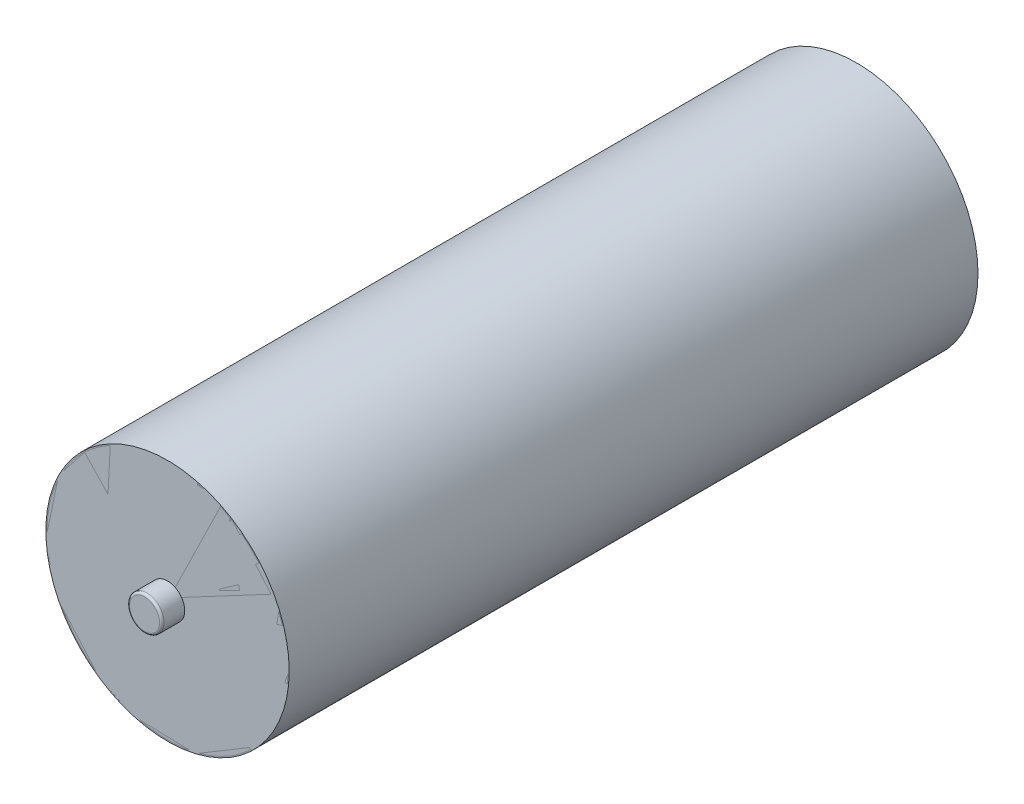
SolidWorks part; units mm, degrees
other "COLL.CYLINDER-Estrusione-Estrusione6"
ref_plane "Piano frontale" through (0, 0, 0) normal (0, 0, 1) x (1, 0, 0)
ref_plane "Piano superiore" through (0, 0, 0) normal (0, 1, 0) x (1, 0, 0)
ref_plane "Piano destro" through (0, 0, 0) normal (1, 0, 0) x (0, 0, -1)
sketch "Schizzo1" plane through (0, 0, 0) normal (0, 0, 1) x (1, 0, 0)
  circle A0 centre (0, 0) radius 52.5
  dimension "D1" = 105
extrude "Estrusione-Estrusione1" add sketch "Schizzo1" along normal blind 150
sketch "Schizzo2" plane through (0, 0, 0) normal (0, 0, -1) x (-1, 0, 0)
  circle A0 centre (0, 0) radius 52.5
  dimension "D1" = 105
extrude "Estrusione-Estrusione2" add sketch "Schizzo2" along normal blind 150
sketch3d "Schizzo3D1"
  line L0 (0, 0, 150) -> (0, 0, -150)
  line L1 (0, 0, 150) -> (0, 0, -150) construction
sketch "Schizzo3" plane through (0, 0, -150) normal (0, 0, -1) x (-1, 0, 0)
  circle A0 centre (0, 0) radius 7.5
  dimension "D1" = 15
extrude "Estrusione-Estrusione3" add sketch "Schizzo3" along normal blind 10
fillet "Raccordo1" radius 1 1 edges at (-7.5, 0, -160)
sketch "Schizzo4" plane through (0, 0, 150) normal (0, 0, 1) x (1, 0, 0)
  circle A0 centre (0, 0) radius 7.5
  dimension "D1" = 15
extrude "Estrusione-Estrusione4" add sketch "Schizzo4" along normal blind 10
fillet "Raccordo2" radius 1 1 edges at (7.5, 0, 160)
sketch "Schizzo8" plane through (0, 0, 0) normal (0, 0, 1) x (1, 0, 0)
  circle A0 centre (0, 0) radius 53
  dimension "D1" = 106
extrude "Estrusione-Estrusione6" add sketch "Schizzo8" along normal blind 150 and the other way blind 150 separate body
